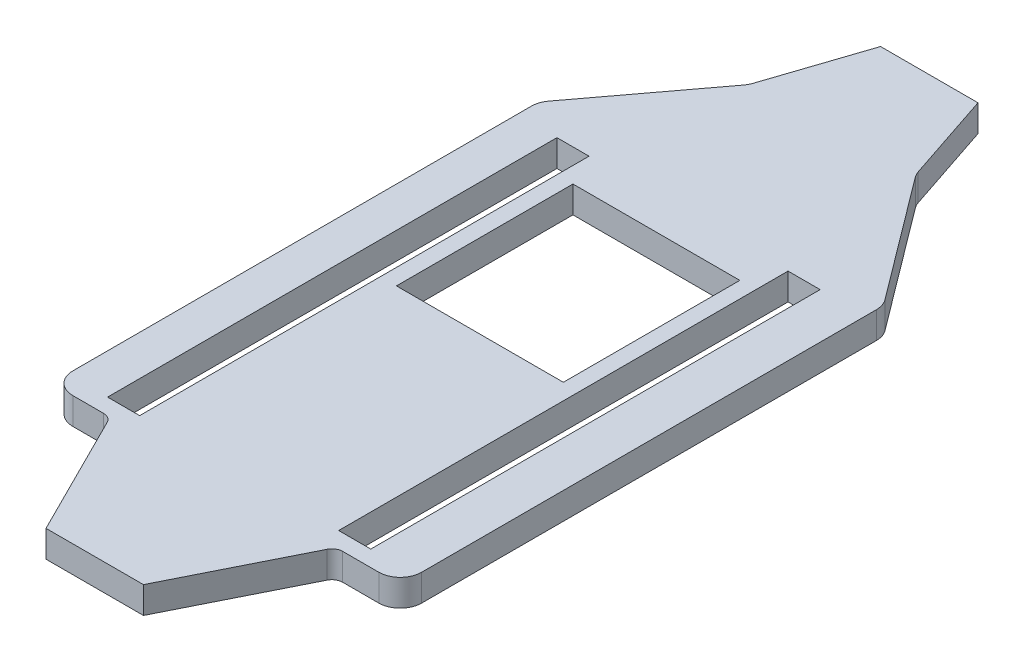
SolidWorks part; units mm, degrees
ref_plane "Front Plane" through (0, 0, 0) normal (0, 0, 1) x (1, 0, 0)
ref_plane "Top Plane" through (0, 0, 0) normal (0, 1, 0) x (1, 0, 0)
ref_plane "Right Plane" through (0, 0, 0) normal (1, 0, 0) x (0, 0, -1)
sketch "Sketch1" plane through (0, 0, 0) normal (0, 1, 0) x (1, 0, 0)
  line L0 (0, 1) -> (0, 22.2522)
  line L1 (0, 22.5855) -> (-4.5513, 22.5855) construction
  line L2 (-4.5513, 22.5855) -> (-4.5513, 28.654) construction
  line L3 (-0.2, 22.8522) -> (-4.454, 28.5241)
  line L4 (-4.5513, 28.654) -> (-6, 28.654) construction
  line L5 (-6, 28.654) -> (-6, 33) construction
  line L6 (-4.6026, 28.8079) -> (-6, 33)
  line L7 (-6, 33) -> (-10.5541, 33)
  line L8 (-10.5541, 28.3702) -> (-10.5541, 33) construction
  line L9 (-10.5541, 28.3702) -> (-12.0974, 28.3702) construction
  line L10 (-12.0974, 28.3702) -> (-12.0974, 22.7667) construction
  line L11 (-12.0974, 22.7667) -> (-16.3, 22.7667) construction
  line L12 (-12.046, 28.5241) -> (-10.5541, 33)
  line L13 (-12.1947, 28.2404) -> (-16.1, 23.0333)
  line L14 (-16.3, 22.4333) -> (-16.3, 1)
  line L15 (-15.3, 0) -> (-13.8631, 0)
  line L16 (-13.5541, 0) -> (-13.5541, -6) construction
  line L17 (-13.5541, -6) -> (-10.5541, -6) construction
  line L18 (-13.4159, -0.2764) -> (-10.5541, -6)
  line L19 (-10.5541, -6) -> (-6, -6)
  line L20 (-6, -6) -> (-3, -6) construction
  line L21 (-3, -6) -> (-3, 0) construction
  line L22 (-6, -6) -> (-3.1382, -0.2764)
  line L23 (-2.691, 0) -> (-1, 0)
  line L24 (-3.627, 21.75) -> (-4.377, 21.75) construction
  line L37 (-8.277, 33) -> (-8.277, -6) construction
  line L38 (-14.427, 0.75) -> (-12.927, 0.75)
  line L39 (-14.427, 0.75) -> (-14.427, 21.75)
  line L40 (-14.427, 21.75) -> (-12.927, 21.75)
  line L41 (-12.927, 0.75) -> (-12.927, 21.75)
  line L42 (-2.127, 21.75) -> (-3.627, 21.75)
  line L43 (-3.627, 0.75) -> (-3.627, 21.75)
  line L44 (-2.127, 0.75) -> (-3.627, 0.75)
  line L45 (-2.127, 0.75) -> (-2.127, 21.75)
  line L46 (-4.377, 21.75) -> (-4.377, 20.2478) construction
  line L47 (-4.377, 20.2478) -> (-12.177, 20.2478)
  line L48 (-12.177, 20.2478) -> (-12.177, 12)
  line L49 (-12.177, 12) -> (-4.377, 12)
  line L50 (-4.377, 12) -> (-4.377, 20.2478)
  arc A0 (0, 22.2522) -> (-0.2, 22.8522) centre (-1, 22.2522) ccw
  arc A1 (-16.3, 22.4333) -> (-16.1, 23.0333) centre (-15.3, 22.4333) cw
  arc A2 (-12.046, 28.5241) -> (-12.1947, 28.2404) centre (-12.9947, 28.8404) cw
  arc A3 (-4.6026, 28.8079) -> (-4.454, 28.5241) centre (-3.654, 29.1241) ccw
  arc A4 (0, 1) -> (-1, 0) centre (-1, 1) cw
  arc A5 (-16.3, 1) -> (-15.3, 0) centre (-15.3, 1) ccw
  arc A6 (-2.691, 0) -> (-3.1382, -0.2764) centre (-2.691, -0.5) ccw
  arc A7 (-13.8631, 0) -> (-13.4159, -0.2764) centre (-13.8631, -0.5) cw
  point P44 (0, 0)
  point P59 (-12.1947, 20.2403)
  dimension "D1" = 0.5
  dimension "D2" = 1
  dimension "D3" = 1
  dimension "D5" = 1
extrude "Boss-Extrude1" add sketch "Sketch1" along normal blind 1.25
